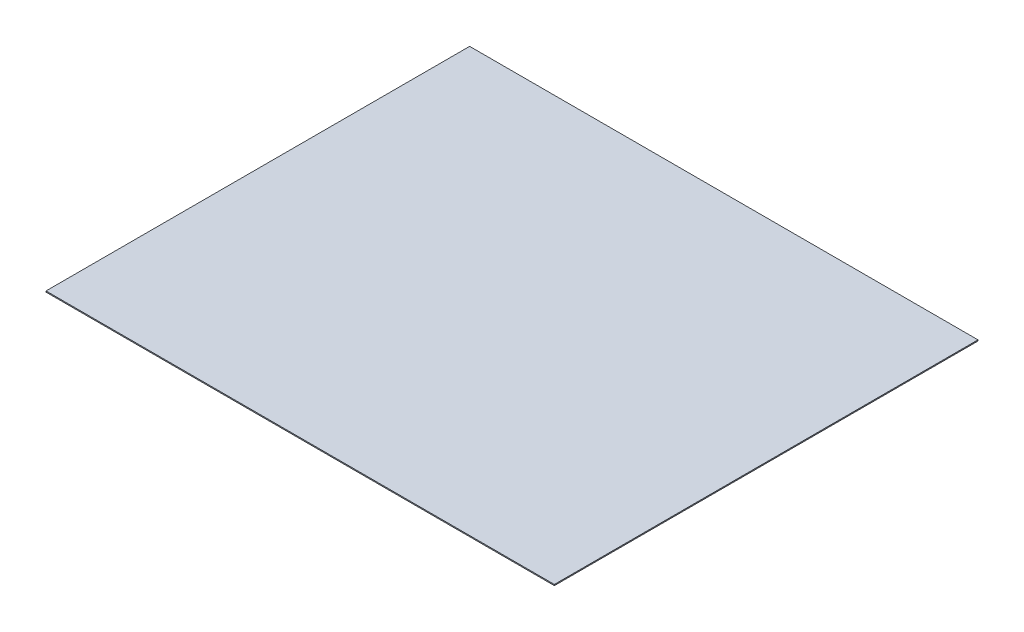
SolidWorks part; units mm, degrees
ref_plane "Front Plane" through (0, 0, 0) normal (0, 0, 1) x (1, 0, 0)
ref_plane "Top Plane" through (0, 0, 0) normal (0, 1, 0) x (1, 0, 0)
ref_plane "Right Plane" through (0, 0, 0) normal (1, 0, 0) x (0, 0, -1)
sketch "Sketch1" plane through (0, 0, 0) normal (0, 1, 0) x (1, 0, 0)
  line L1 (1200, -1000) -> (-1200, -1000)
  line L2 (1200, -1000) -> (1200, 1000)
  line L3 (1200, 1000) -> (-1200, 1000)
  line L4 (-1200, -1000) -> (-1200, 1000)
  line L5 (1200, -1000) -> (-1200, 1000) construction
  line L6 (1200, 1000) -> (-1200, -1000) construction
  point P0 (0, 0)
  dimension "D1" = 2400
  dimension "D2" = 2000
extrude "Boss-Extrude1" add sketch "Sketch1" along normal blind 5
